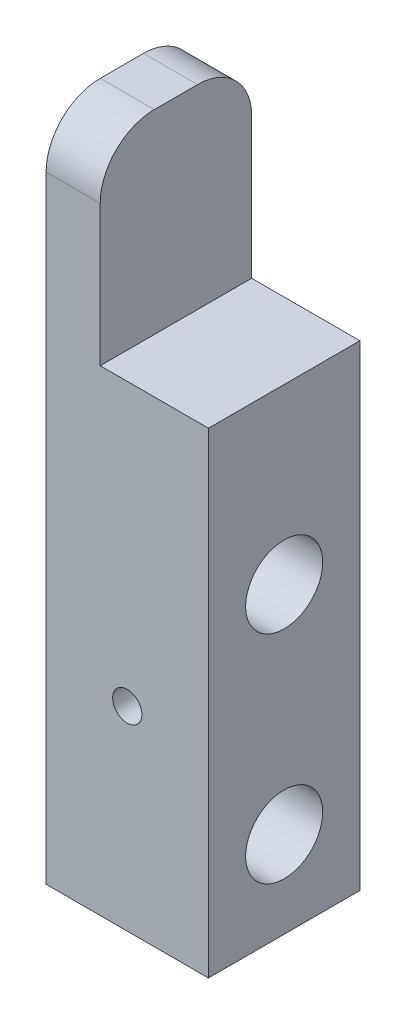
SolidWorks part; units mm, degrees
ref_plane "前视基准面" through (0, 0, 0) normal (0, 0, 1) x (1, 0, 0)
ref_plane "上视基准面" through (0, 0, 0) normal (0, 1, 0) x (1, 0, 0)
ref_plane "右视基准面" through (0, 0, 0) normal (1, 0, 0) x (0, 0, -1)
sketch "草图1" plane through (0, 0, 0) normal (0, 0, 1) x (1, 0, 0)
  line L1 (-7.5, -18) -> (7.5, -18)
  line L2 (-7.5, -18) -> (-7.5, 21)
  line L4 (7.5, -18) -> (7.5, 23)
  line L8 (-7.5, 21) -> (-7.5, 26)
  line L9 (-2.5, 26) -> (7.5, 26)
  line L10 (7.5, 23) -> (7.5, 26)
  line L12 (-7.5, 26) -> (-7.5, 44)
  line L13 (-7.5, 44) -> (-2.5, 44)
  line L14 (-2.5, 26) -> (-2.5, 44)
  point P0 (0, 0)
  dimension "D1" = 26
  dimension "D2" = 15
  dimension "D3" = 18
  dimension "D4" = 5
  dimension "D5" = 18
  dimension "D8" = 7.5
extrude "凸台-拉伸1" add sketch "草图1" along normal mid plane 14 contours L2 L8 L12 L13 L14 L9 L10 L4 L1
sketch "草图3" plane through (7.5, 0, 0) normal (1, 0, 0) x (0, 0, -1)
  circle A0 centre (0, -10) radius 3.56
  circle A1 centre (0, 10) radius 3.56
  dimension "D1" = 7.12
  dimension "D2" = 7.12
  dimension "D3" = 10
  dimension "D4" = 10
extrude "切除-拉伸1" cut sketch "草图3" against normal blind 20
sketch "草图4" plane through (0, 0, 7) normal (0, 0, 1) x (1, 0, 0)
  circle A0 centre (0, 0) radius 1.35
  dimension "D1" = 2.7
extrude "切除-拉伸2" cut sketch "草图4" against normal blind 14
fillet "圆角1" radius 5 2 edges at (-5, 44, -7) (-5, 44, 7)
